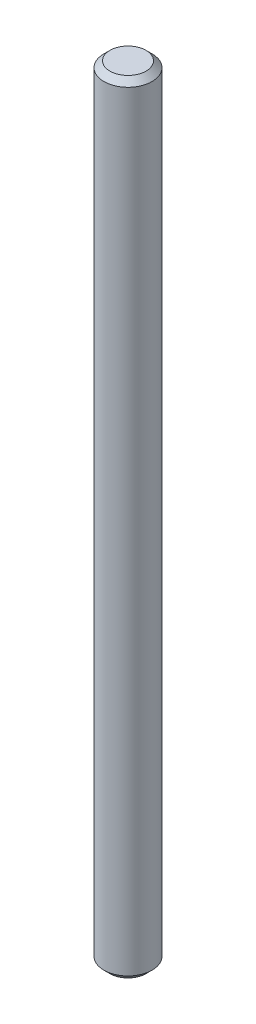
SolidWorks part; units mm, degrees
material "Plain Carbon Steel"
ref_plane "Front Plane" through (0, 0, 0) normal (0, 0, 1) x (1, 0, 0)
ref_plane "Top Plane" through (0, 0, 0) normal (0, 1, 0) x (1, 0, 0)
ref_plane "Right Plane" through (0, 0, 0) normal (1, 0, 0) x (0, 0, -1)
sketch "Sketch1" plane through (0, 0, 0) normal (0, 1, 0) x (1, 0, 0)
  circle A0 centre (0, 0) radius 4
  dimension "D1" = 8
extrude "Boss-Extrude1" add sketch "Sketch1" along normal mid plane 130
chamfer "Chamfer1" distance 1 angle 45 2 edges at (0, 65, 4) (0, -65, 4)
